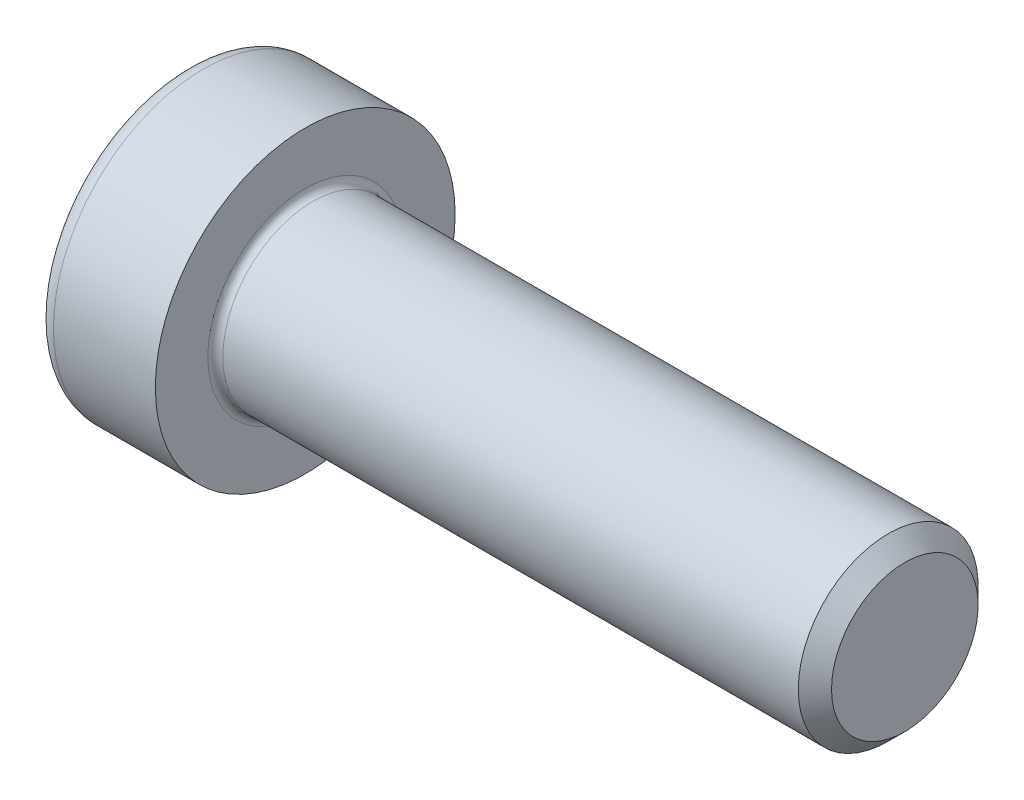
SolidWorks part; units mm, degrees
revolve "Base-Revolve" add sketch "BodySke"
sketch "BodySke" plane through (0, 0, 0) normal (0, 0, 1) x (1, 0, 0)
  line L0 (0, 0) -> (0, 5)
  line L1 (0, 5) -> (4, 5)
  line L2 (4, 5) -> (4, 3)
  line L3 (4, 3) -> (23.4455, 3)
  line L4 (24, 2.4455) -> (24, 0)
  line L5 (24, 0) -> (0, 0)
  line L6 (-31.75, 0) -> (127, 0) construction
  line L8 (24, 2.4455) -> (23.4455, 3)
  line L10 (24, -2.4455) -> (23.4455, -3) construction
  line L11 (5, 4.525) -> (5, -1.825) construction
  line L12 (7, 4.525) -> (7, -1.825) construction
  line L13 (-36, 4.525) -> (-36, -1.825) construction
  dimension "Head_ht" = 4
  dimension "Length" = 20
  dimension "Body_ch_ang" = 45
  dimension "Diameter" = 6
  dimension "Minor_dia" = 4.891
  dimension "Advance" = 1
  dimension "Thread_nom" = 17
  dimension "Thread_length" = 60
  dimension "Head_dia" = 10
cosmetic thread "ThreadCosmetic"
fillet "Fillet1" radius 0.25 1 edges at (4, 0, 3)
fillet "Fillet2" radius 0.6 1 edges at (0, 0, 5)
material "AISI 316 Нержавеющая сталь, лист (SS)"
ref_plane "Plane1" through (0, 0, 0) normal (0, 0, 1) x (1, 0, 0)
ref_plane "Plane2" through (0, 0, 0) normal (0, 1, 0) x (1, 0, 0)
ref_plane "Plane3" through (0, 0, 0) normal (1, 0, 0) x (0, 0, -1)
other "Configuration Table"
sketch "Sketch2" plane through (0, 0, 0) normal (0, 0, 1) x (1, 0, 0)
  line L0 (0, 2) -> (3, 2)
  line L1 (3, 2) -> (4.1547, 0)
  line L2 (-31.75, 0) -> (127, 0) construction
  line L3 (4.1547, 0) -> (0, 0)
  line L4 (0, 0) -> (0, 2)
  line L6 (0, 0) -> (47.625, 0) construction
  dimension "D1" = 2
  dimension "D2" = 60
  dimension "Depth" = 3
revolve "Hex-PreBroach" cut sketch "Sketch2" angle 360 about L6
sketch "Sketch3" plane through (0, 0, 0) normal (-1, 0, 0) x (0, 0.5, 0.866)
  line L0 (1.1547, 2) -> (-1.1547, 2)
  line L1 (-1.1547, 2) -> (-2.3094, 0)
  line L2 (1.1547, 2) -> (2.3094, 0)
  line L3 (1.1547, -2) -> (2.3094, 0)
  line L4 (1.1547, -2) -> (-1.1547, -2)
  line L5 (-1.1547, -2) -> (-2.3094, 0)
  dimension "D1" = 2
  dimension "D2" = 2
  dimension "Hex_size" = 4
extrude "Hex" cut sketch "Sketch3" against normal blind 3
sketch "ThdSchSke" plane through (0, 0, 0) normal (0, 0, 1) x (1, 0, 0)
  line L0 (7, -2.4455) -> (6.6117, -3)
  line L1 (7, -2.4455) -> (7.3883, -3)
  line L2 (7.3883, -3) -> (7.3883, -3.75)
  line L3 (-3.175, 0) -> (5.1513, 0) construction
  line L4 (0, 4.4) -> (0, -4.4) construction
  line L5 (7.3883, -3.75) -> (6.6117, -3.75)
  line L6 (6.6117, -3.75) -> (6.6117, -3)
  dimension "Thread_minor" = 4.891
  dimension "Diameter" = 6
  dimension "Start" = 7
revolve "ThreadSchematic" [suppressed] cut sketch "ThdSchSke" angle 360 about L3
pattern_linear "ThdSchPat" [suppressed]
equation "\"D2@Sketch3\" = \"Hex_size@Sketch3\" / 2"
equation "\"D1@Sketch3\" = \"Hex_size@Sketch3\" / 2"
equation "\"D1@Sketch2\" = \"Hex_size@Sketch3\" / 2"
equation "\"Thread_minor@ThreadCosmetic\"  =  \"Minor_dia@BodySke\""
equation "\"Depth@Sketch2\" =  \"Key_eng@Hex\""
equation "\"Thread_length@ThreadCosmetic\" = ((sgn( (\"Length@BodySke\" - \"Advance@BodySke\" * 3.0) - \"Thread_nom@BodySke\" )-1)*( (\"Length@BodySke\" - \"Advance@BodySke\" * 3.0) - \"Thread_nom@BodySke\" ))/-2+ \"Thread_nom@BodySke\""
equation "\"Thread_minor@ThdSchSke\" = \"Minor_dia@BodySke\""
equation "\"Diameter@ThdSchSke\" = \"Diameter@BodySke\""
equation "\"Overcut@ThdSchSke\" = \"Diameter@BodySke\" * 1.25"
equation "\"Start@ThdSchSke\" = \"Head_ht@BodySke\" + \"Length@BodySke\" - \"Thread_length@ThreadCosmetic\"  '---Non-countersunk---"
equation "\"Num_threads@ThdSchPat\" = int( \"Thread_length@ThreadCosmetic\" / \"Advance@BodySke\" + 0.999 )  + 1"
equation "\"Advance@ThdSchPat\" = \"Thread_length@ThreadCosmetic\" /  (\"Num_threads@ThdSchPat\" - 1) 'relax it"
equation "\"Num_threads@ThdSchPat\" = \"Num_threads@ThdSchPat\" - sgn( \"Num_threads@ThdSchPat\" - 1) '---chamfered tips only---"
